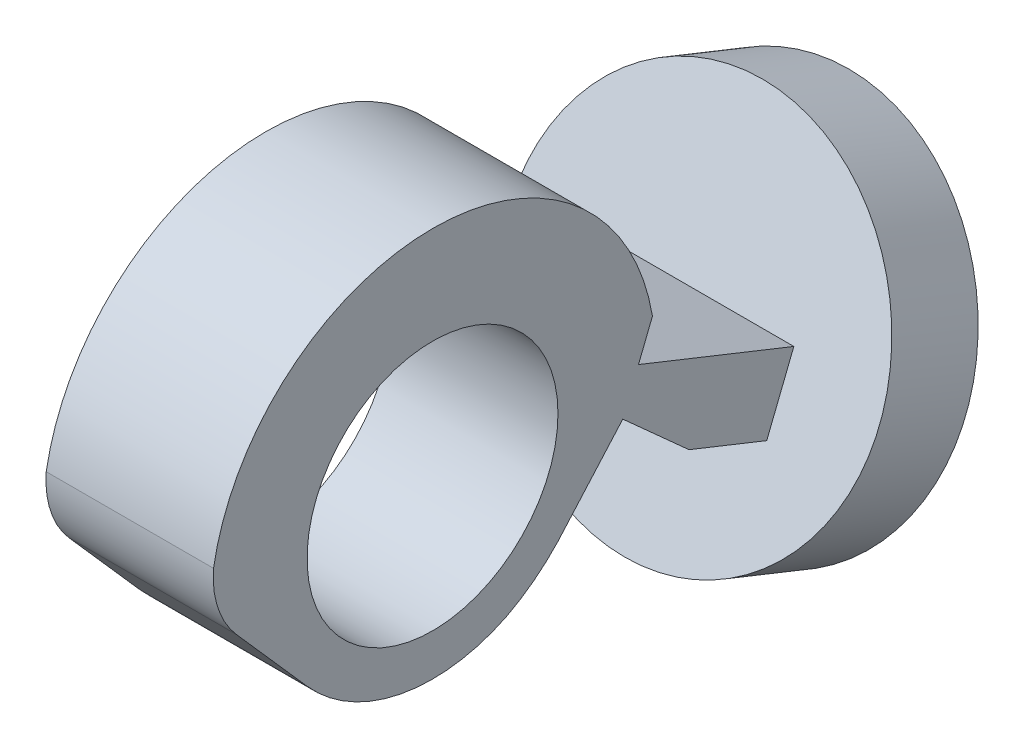
SolidWorks part; units mm, degrees
ref_plane "Front Plane" through (0, 0, 0) normal (0, 0, 1) x (1, 0, 0)
ref_plane "Top Plane" through (0, 0, 0) normal (0, 1, 0) x (1, 0, 0)
ref_plane "Right Plane" through (0, 0, 0) normal (1, 0, 0) x (0, 0, -1)
sketch "Sketch1" plane through (0, 0, 0) normal (1, 0, 0) x (0, 0, -1)
  line L0 (-0.4549, 12.3594) -> (3.3447, 8.051)
  line L1 (16.8447, 8.051) -> (20.3309, 12.0039)
  line L2 (20.3309, 12.0039) -> (21.9269, 16.0039)
  arc A0 (21.9269, 16.0039) -> (-1.6892, 16.0631) centre (10.1138, 14.0255) ccw
  arc A1 (-1.6892, 16.0631) -> (-0.4549, 12.3594) centre (3.2951, 15.6666) ccw
  arc A2 (3.3447, 8.051) -> (14.0632, 5.9261) centre (10.0947, 14.0039) ccw
  arc A3 (14.0632, 5.9261) -> (16.8447, 8.051) centre (9.3673, 14.9561) ccw
  circle A4 centre (10.0947, 14.0039) radius 6.75
extrude "Boss-Extrude1" add sketch "Sketch1" along normal blind 9
ref_plane "Plane1" through (0, 5, 0) normal (0, 1, 0) x (1, 0, 0)
sketch "Sketch3" plane through (0, -5.3494, -13.407) normal (0, -0.3706, -0.9288) x (-1, 0, 0)
  circle A0 centre (-4, 19.907) radius 10
  point P2 (-4, 19.907)
extrude "Boss-Extrude2" add sketch "Sketch3" along normal blind 14
sketch "Sketch4" plane through (0, -5.3494, -13.407) normal (0, 0.3706, 0.9288) x (1, 0, 0)
  line L0 (0, 23.9649) -> (9, 23.9649)
  line L1 (0, 28.7525) -> (0, 14.2934) construction
  line L2 (9, 14.2934) -> (9, 28.7525) construction
  line L3 (9, 23.9649) -> (9, 15.0252)
  line L4 (9, 15.0252) -> (0, 15.0252)
  line L5 (0, 15.0252) -> (0, 23.9649)
  circle A0 centre (4, 19.907) radius 10
extrude "Cut-Extrude1" cut sketch "Sketch4" against normal blind 9
sketch "Sketch5" plane through (0, 22.2585, -8.8811) normal (0, 0.9288, -0.3706) x (1, 0, 0)
  line L1 (0, 23.4348) -> (9, 23.4348)
  line L2 (0, 23.4348) -> (0, 14.4348)
  line L3 (0, 14.4348) -> (9, 14.4348)
  line L4 (9, 23.4348) -> (9, 14.4348)
  line L5 (0, 23.4348) -> (9, 14.4348) construction
  line L6 (0, 14.4348) -> (9, 23.4348) construction
  point P4 (4.5, 18.9348)
extrude "Cut-Extrude2" cut sketch "Sketch5" against normal blind 3
sketch "Sketch6" plane through (0, 13.9554, -5.5682) normal (0, -0.9288, 0.3706) x (1, 0, 0)
  line L1 (0, -14.4348) -> (9, -14.4348)
  line L2 (0, -14.4348) -> (0, -23.4348)
  line L3 (0, -23.4348) -> (9, -23.4348)
  line L4 (9, -14.4348) -> (9, -23.4348)
  line L5 (0, -14.4348) -> (9, -23.4348) construction
  line L6 (0, -23.4348) -> (9, -14.4348) construction
  point P4 (4.5, -18.9348)
extrude "Cut-Extrude4" cut sketch "Sketch6" against normal blind 2
sketch "Sketch7" plane through (0, 0, 0) normal (-1, 0, 0) x (0, 0, 1)
  line L0 (-20.3309, 12.0039) -> (-23.8959, 8.796)
  line L1 (-19.7163, 10.4636) -> (-28.0755, 7.1283) construction
  line L2 (-23.8959, 8.796) -> (-19.7163, 10.4636)
  line L3 (-19.7163, 10.4636) -> (-20.3309, 12.0039)
extrude "Cut-Extrude5" cut sketch "Sketch7" against normal blind 10
sketch "Sketch8" plane through (0, -10.5376, -26.4101) normal (0, -0.3706, -0.9288) x (-1, 0, 0)
  line L4 (-4, 29.907) -> (-4, 9.907) construction
  line L5 (-14, 19.907) -> (6, 19.907) construction
  line L7 (-6.5, 16.907) -> (-1.5, 16.907)
  line L8 (-6.5, 16.907) -> (-6.5, 22.907)
  line L9 (-6.5, 22.907) -> (-1.5, 22.907)
  line L10 (-1.5, 16.907) -> (-1.5, 22.907)
  line L11 (-6.5, 16.907) -> (-1.5, 22.907) construction
  line L12 (-6.5, 22.907) -> (-1.5, 16.907) construction
  circle A0 centre (-4, 19.907) radius 10 construction
  point P7 (-4, 19.907)
  dimension "D1" = 5
  dimension "D2" = 6
extrude "Cut-Extrude6" cut sketch "Sketch8" against normal blind 3
